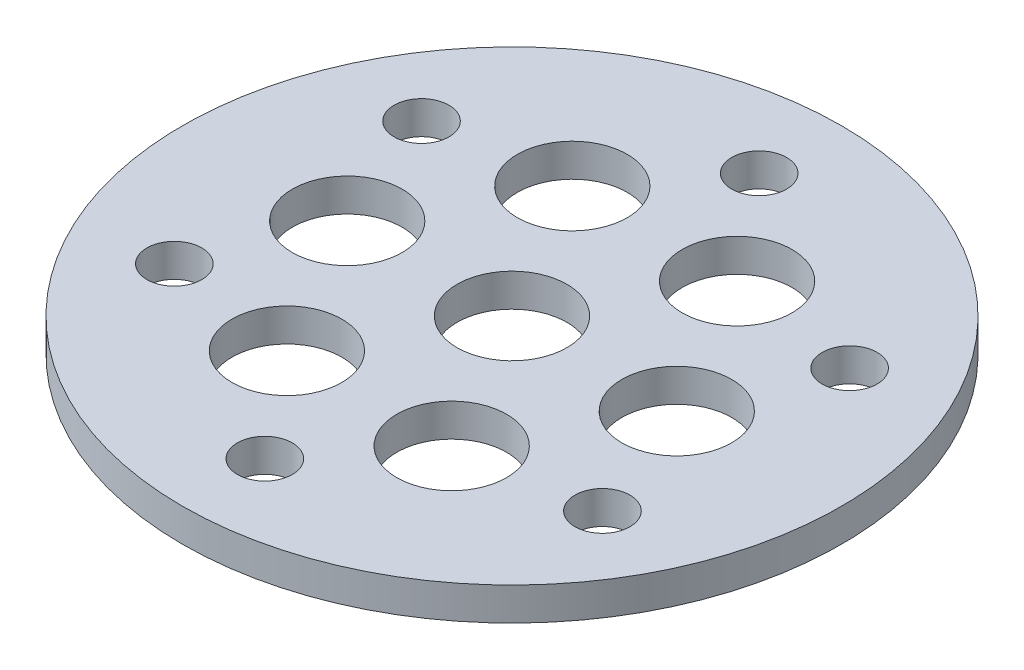
SolidWorks part; units mm, degrees
material "Thornel Mat VMA"
ref_plane "前视基准面" through (0, 0, 0) normal (0, 0, 1) x (1, 0, 0)
ref_plane "上视基准面" through (0, 0, 0) normal (0, 1, 0) x (1, 0, 0)
ref_plane "右视基准面" through (0, 0, 0) normal (1, 0, 0) x (0, 0, -1)
sketch "草图1" plane through (0, 0, 0) normal (0, 1, 0) x (1, 0, 0)
  circle A0 centre (0, 0) radius 30
  circle A1 centre (0, 0) radius 22.5 construction
  circle A2 centre (0, 0) radius 5
  circle A3 centre (0, 22.5) radius 2.5
  circle A4 centre (19.4856, 11.25) radius 2.5
  circle A5 centre (19.4856, -11.25) radius 2.5
  circle A6 centre (0, -22.5) radius 2.5
  circle A7 centre (-19.4856, -11.25) radius 2.5
  circle A8 centre (-19.4856, 11.25) radius 2.5
  circle A9 centre (-7.5, 12.9904) radius 5
  circle A10 centre (0, 0) radius 15 construction
  circle A11 centre (7.5, 12.9904) radius 5
  circle A12 centre (15, 0) radius 5
  circle A13 centre (7.5, -12.9904) radius 5
  circle A14 centre (-7.5, -12.9904) radius 5
  circle A15 centre (-15, 0) radius 5
  point P19 (0, 0)
  point P21 (4.2115, 11.25)
  dimension "D1" = 60
  dimension "D2" = 45
  dimension "D3" = 10
  dimension "D4" = 5
  dimension "D6" = 10
  dimension "D7" = 30
  dimension "D5" = 6
extrude "凸台-拉伸1" add sketch "草图1" along normal blind 3
